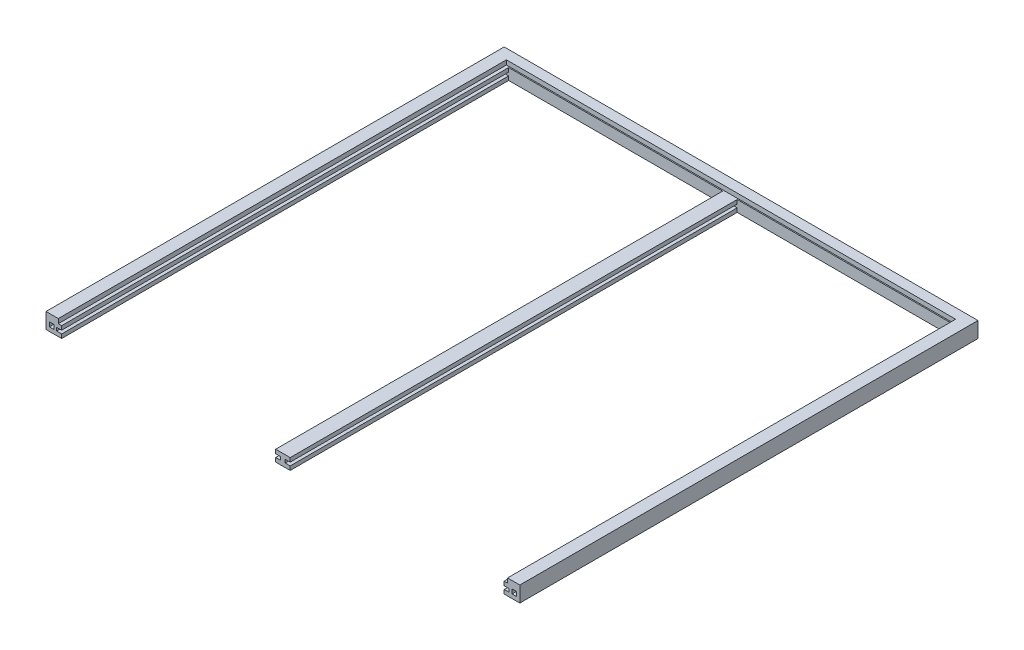
SolidWorks part; units mm, degrees
ref_plane "Front Plane" through (0, 0, 0) normal (0, 0, 1) x (1, 0, 0)
ref_plane "Top Plane" through (0, 0, 0) normal (0, 1, 0) x (1, 0, 0)
ref_plane "Right Plane" through (0, 0, 0) normal (1, 0, 0) x (0, 0, -1)
sketch "Sketch1" plane through (0, 0, 0) normal (0, 0, 1) x (1, 0, 0)
  line L0 (106, 0) -> (106, 5)
  line L1 (0, 0) -> (212, 0)
  line L2 (0, 0) -> (0, 5)
  line L3 (0, 5) -> (212, 5)
  line L4 (212, 0) -> (212, 5)
  line L5 (0, 5) -> (7, 5)
  line L6 (0, 5) -> (0, 0)
  line L7 (0, 0) -> (7, 0)
  line L8 (7, 5) -> (7, 0)
  line L9 (212, 5) -> (205, 5)
  line L10 (212, 5) -> (212, 0)
  line L11 (212, 0) -> (205, 0)
  line L12 (205, 5) -> (205, 0)
  line L13 (7, 3.225) -> (4.75, 3.225)
  line L14 (7, 3.225) -> (7, 1.775)
  line L15 (7, 1.775) -> (4.75, 1.775)
  line L16 (4.75, 3.225) -> (4.75, 1.775)
  line L17 (205, 1.775) -> (207.25, 1.775)
  line L18 (102.75, 5) -> (109.25, 5)
  line L19 (102.75, 5) -> (102.75, 0)
  line L20 (102.75, 0) -> (109.25, 0)
  line L21 (109.25, 5) -> (109.25, 0)
  line L22 (102.75, 3.225) -> (105, 3.225)
  line L23 (102.75, 3.225) -> (102.75, 1.775)
  line L24 (102.75, 1.775) -> (105, 1.775)
  line L25 (105, 3.225) -> (105, 1.775)
  line L26 (109.25, 3.225) -> (107, 3.225)
  line L27 (109.25, 3.225) -> (109.25, 1.775)
  line L28 (109.25, 1.775) -> (107, 1.775)
  line L29 (107, 3.225) -> (107, 1.775)
  line L30 (207.25, 3.225) -> (207.25, 1.775)
  line L31 (205, 3.225) -> (207.25, 3.225)
  line L32 (205, 3.225) -> (205, 1.775)
  dimension "D1" = 5
  dimension "D2" = 212
  dimension "D3" = 7
  dimension "D4" = 7
  dimension "D5" = 2.25
  dimension "D6" = 1.775
  dimension "D7" = 1.45
  dimension "D8" = 1.775
  dimension "D9" = 3.25
  dimension "D10" = 3.25
  dimension "D11" = 2.25
  dimension "D12" = 2.25
  dimension "D13" = 1.775
  dimension "D14" = 1.45
  dimension "D15" = 1.45
  dimension "D16" = 1.775
extrude "Boss-Extrude1" add sketch "Sketch1" along normal blind 5 contours L16 L13 L8 L3 L2 L1 L15 | L13 L16 L15 L8 | L19 L3 L8 L1 | L25 L22 L19 L24 | L22 L25 L24 L19 L1 L0 L3 | L29 L26 L21 L3 L0 L1 L28 | L26 L29 L28 L21 | L3 L21 L1 L12 | L31 L12 L17 L30 | L12 L31 L30 L17 L1 L4 L3
sketch "Sketch2" plane through (0, 0, 5) normal (0, 0, 1) x (1, 0, 0)
  line L0 (205, 3.225) -> (207.25, 3.225) construction
  line L1 (207.25, 3.225) -> (207.25, 1.775) construction
  line L2 (205, 1.775) -> (207.25, 1.775) construction
  line L3 (205, 5) -> (205, 0) construction
  line L4 (109.25, 5) -> (109.25, 0) construction
  line L5 (109.25, 3.225) -> (107, 3.225) construction
  line L6 (109.25, 1.775) -> (107, 1.775) construction
  line L7 (107, 3.225) -> (107, 1.775) construction
  line L8 (102.75, 1.775) -> (105, 1.775) construction
  line L9 (105, 3.225) -> (105, 1.775) construction
  line L10 (102.75, 3.225) -> (105, 3.225) construction
  line L11 (102.75, 5) -> (102.75, 0) construction
  line L12 (7, 5) -> (7, 0) construction
  line L13 (7, 1.775) -> (4.75, 1.775) construction
  line L14 (4.75, 3.225) -> (4.75, 1.775) construction
  line L15 (7, 3.225) -> (4.75, 3.225) construction
  line L16 (205, 3.225) -> (207.25, 3.225)
  line L17 (207.25, 3.225) -> (207.25, 1.775)
  line L18 (205, 1.775) -> (207.25, 1.775)
  line L19 (205, 5) -> (205, 0)
  line L20 (109.25, 5) -> (109.25, 0)
  line L21 (109.25, 3.225) -> (107, 3.225)
  line L22 (109.25, 1.775) -> (107, 1.775)
  line L23 (107, 3.225) -> (107, 1.775)
  line L24 (102.75, 1.775) -> (105, 1.775)
  line L25 (105, 3.225) -> (105, 1.775)
  line L26 (102.75, 3.225) -> (105, 3.225)
  line L27 (102.75, 5) -> (102.75, 0)
  line L28 (7, 5) -> (7, 0)
  line L29 (7, 1.775) -> (4.75, 1.775)
  line L30 (4.75, 3.225) -> (4.75, 1.775)
  line L31 (7, 3.225) -> (4.75, 3.225)
  line L36 (212, 0) -> (212, 5)
  line L37 (212, 5) -> (0, 5)
  line L38 (0, 5) -> (0, 0)
  line L39 (0, 0) -> (212, 0)
  line L40 (212, 0) -> (212, 5)
  line L41 (212, 5) -> (0, 5)
  line L42 (0, 5) -> (0, 0)
  line L43 (0, 0) -> (212, 0)
  line M5 (212, 0) -> (212, 5)
  line M6 (212, 5) -> (0, 5)
  line M7 (0, 5) -> (0, 0)
  line M8 (0, 0) -> (212, 0)
  dimension "D1" = 0
extrude "Boss-Extrude2" add sketch "Sketch2" along normal blind 200 contours L31 L28 L29 L30 M6 M7 M8 | L27 L26 L25 L24 L20 L22 L23 L21 M6 M8 | L19 L16 L17 L18 M6 M8 M5
sketch "Sketch3" plane through (0, 5, 0) normal (0, 1, 0) x (1, 0, 0)
  line L0 (212, -205) -> (205, -205) construction
  line L1 (5.5, -4.5) -> (206.5, -4.5)
  line L2 (5.5, -4.5) -> (5.5, -205)
  line L3 (5.5, -205) -> (206.5, -205)
  line L4 (206.5, -4.5) -> (206.5, -205)
  line L6 (212, 0) -> (0, 0)
  line L7 (212, 0) -> (212, -205)
  line L8 (212, -205) -> (0, -205)
  line L9 (0, 0) -> (0, -205)
  line M7 (212, 0) -> (0, 0)
  line M8 (0, 0) -> (0, -205)
  line M9 (0, -205) -> (7, -205)
  line M17 (205, -205) -> (212, -205)
  line M18 (212, -205) -> (212, 0)
  dimension "D1" = 4.5
  dimension "D2" = 5.5
  dimension "D3" = 5.5
extrude "Boss-Extrude3" add sketch "Sketch3" along normal blind 2 contours L1 L4 L2 M17 M18 M7 M8 M9
sketch "Sketch4" plane through (0, 0, 205) normal (0, 0, 1) x (1, 0, 0)
  line L0 (0, 7) -> (0, 0) construction
  line L1 (1.5, 1.7685) -> (3.5, 1.7685)
  line L2 (1.5, 1.7685) -> (1.5, 3.7685)
  line L3 (1.5, 3.7685) -> (3.5, 3.7685)
  line L4 (3.5, 1.7685) -> (3.5, 3.7685)
  line L6 (106, 5) -> (106, 0)
  line L7 (109.25, 5) -> (102.75, 5) construction
  line L8 (102.75, 0) -> (109.25, 0) construction
  line L9 (210.5, 3.7685) -> (208.5, 3.7685)
  line L10 (208.5, 1.7685) -> (208.5, 3.7685)
  line L11 (210.5, 1.7685) -> (208.5, 1.7685)
  line L12 (210.5, 1.7685) -> (210.5, 3.7685)
  dimension "D1" = 2
  dimension "D2" = 2
  dimension "D3" = 1.5
extrude "Cut-Extrude1" cut sketch "Sketch4" against normal blind 3 contours L11 L12 L9 L10 | L1 L4 L3 L2
